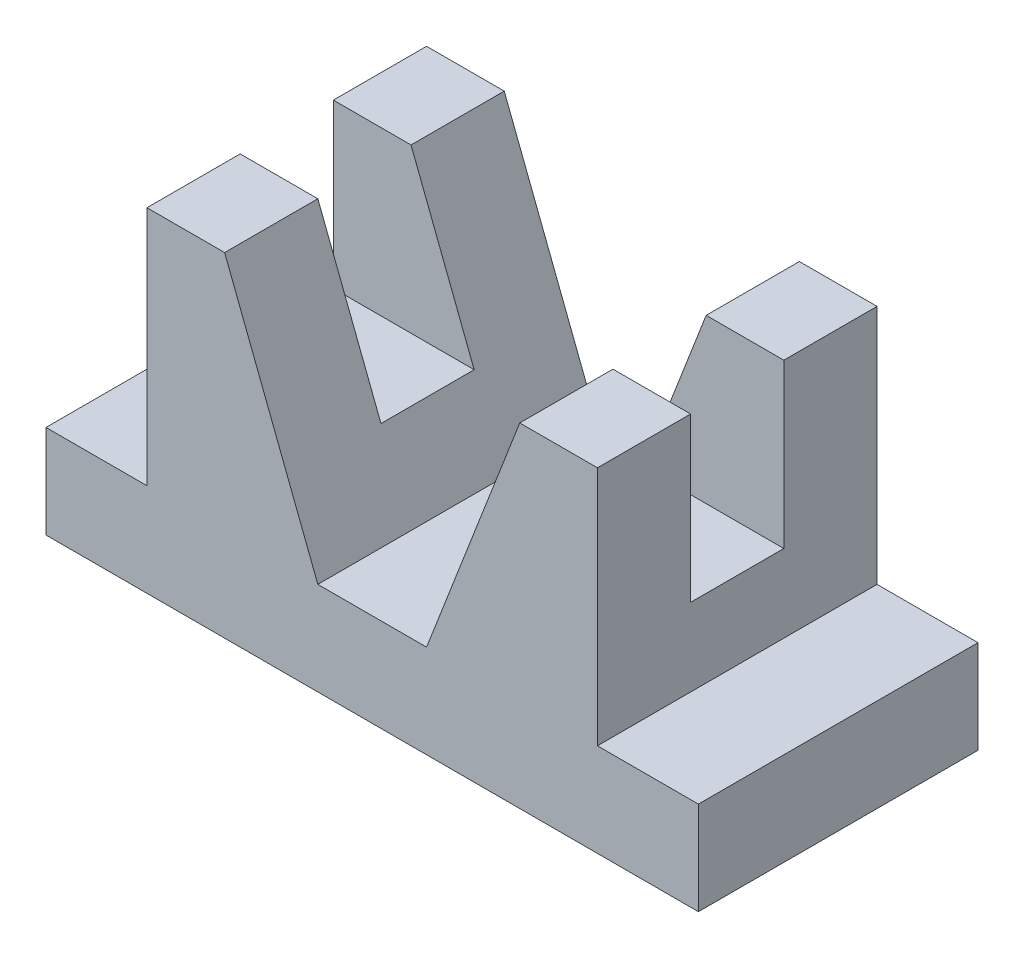
SolidWorks part; units mm, degrees
ref_plane "Alzado" through (0, 0, 0) normal (0, 0, 1) x (1, 0, 0)
ref_plane "Planta" through (0, 0, 0) normal (0, 1, 0) x (1, 0, 0)
ref_plane "Vista lateral" through (0, 0, 0) normal (1, 0, 0) x (0, 0, -1)
sketch "Croquis1" plane through (0, 0, 0) normal (0, 0, 1) x (1, 0, 0)
  line L0 (-29, 6) -> (-29, 37)
  line L1 (-42, 6) -> (-29, 6)
  line L2 (-42, 6) -> (-42, -6)
  line L3 (-42, -6) -> (42, -6)
  line L4 (42, 6) -> (42, -6)
  line L5 (-29, 37) -> (-19, 37)
  line L6 (-19, 37) -> (-7, 6)
  line L7 (0, -41.561) -> (0, 41.561) construction
  line L8 (19, 37) -> (7, 6)
  line L9 (29, 6) -> (29, 37)
  line L10 (29, 37) -> (19, 37)
  line L11 (-7, 6) -> (7, 6)
  line L12 (29, 6) -> (42, 6)
  point P4 (0, -6)
  point P5 (42, 0)
  point P15 (0, 0)
  dimension "D1" = 84
  dimension "D2" = 12
  dimension "D3" = 31
  dimension "D4" = 14
  dimension "D5" = 58
  dimension "D6" = 38
extrude "Saliente-Extruir1" add sketch "Croquis1" against normal blind 36
sketch "Croquis2" plane through (0, 37, 0) normal (0, 1, 0) x (1, 0, 0)
  line L0 (-29, 36) -> (-29, 0) construction
  line L5 (-19, 36) -> (-19, 0) construction
  line L23 (-29, 24) -> (-7, 24)
  line L28 (-29, 24) -> (-29, 12)
  line L35 (29, 36) -> (29, 0) construction
  line L36 (-29, 12) -> (-7, 12)
  line L37 (-7, 24) -> (-7, 12)
  line L38 (-7, 36) -> (-7, 0) construction
  line L39 (7, 36) -> (7, 0) construction
  line L40 (7, 24) -> (29, 24)
  line L41 (7, 24) -> (7, 12)
  line L42 (7, 12) -> (29, 12)
  line L43 (29, 24) -> (29, 12)
  line L44 (-29, 36) -> (-29, 0) construction
  point P16 (29, 18)
  point P20 (29, 18)
  point P23 (-29, 18)
  point P24 (-29, 18)
  dimension "D1" = 12
  dimension "D2" = 12
extrude "Cortar-Extruir2" cut sketch "Croquis2" against normal blind 21
